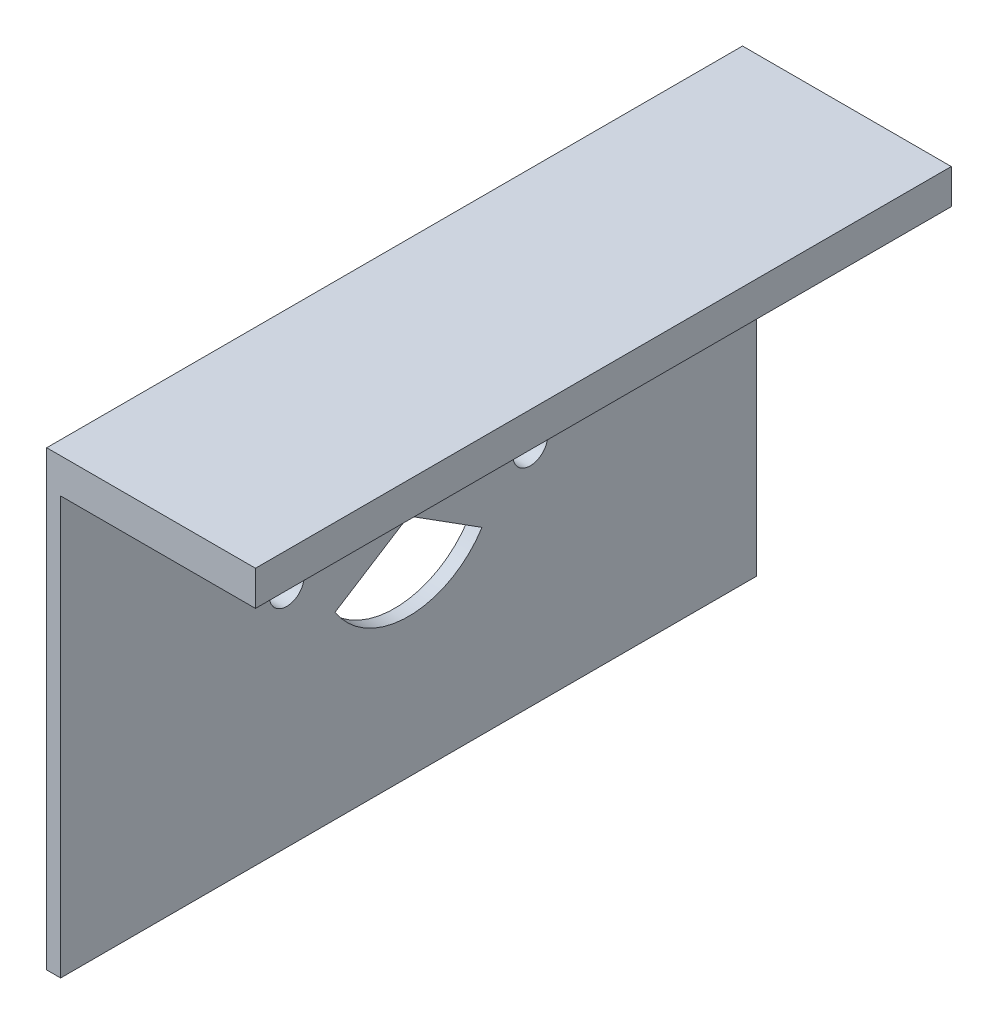
SolidWorks part; units mm, degrees
ref_plane "Front Plane" through (0, 0, 0) normal (0, 0, 1) x (1, 0, 0)
ref_plane "Top Plane" through (0, 0, 0) normal (0, 1, 0) x (1, 0, 0)
ref_plane "Right Plane" through (0, 0, 0) normal (1, 0, 0) x (0, 0, -1)
sketch "Sketch1" plane through (0, 0, 0) normal (1, 0, 0) x (0, 0, -1)
  line L0 (0, 0) -> (-10.5574, -6.6926)
  line L1 (-50, -32.5) -> (50, -32.5)
  line L2 (-50, -32.5) -> (-50, 32.5)
  line L3 (-50, 32.5) -> (50, 32.5)
  line L4 (50, -32.5) -> (50, 32.5)
  line L5 (-50, -32.5) -> (50, 32.5) construction
  line L6 (-50, 32.5) -> (50, -32.5) construction
  line L7 (0, 0) -> (10.5574, -6.6926)
  line L8 (-50, 32.5) -> (-50, 27.5)
  line L9 (-50, 27.5) -> (50, 27.5)
  line L10 (-50, 0) -> (50, 0)
  circle A0 centre (0, 0) radius 12.5
  circle A1 centre (-17.5, 0) radius 2.5
  circle A2 centre (17.5, 0) radius 2.5
  point P0 (0, 0)
  point P8 (-10.5574, -6.6926)
  point P9 (10.5574, -6.6926)
  point P12 (-50, 27.5)
  point P13 (50, 27.5)
  point P18 (-17.5, 0)
  point P19 (17.5, 0)
  dimension "D3" = 25
  dimension "D8" = 5
  dimension "D9" = 5
  dimension "D1" = 100
  dimension "D2" = 65
  dimension "D4" = 5
  dimension "D5" = 5
  dimension "D6" = 17.5
  dimension "D7" = 17.5
extrude "Boss-Extrude5" add sketch "Sketch1" along normal blind 2 contours L2 L9 L4 L3 | A2 L10 L4 L9 L2 A1 A0 | L10 A0 | L10 A0 L0 | L7 A0 L10 | A2 L10 A0 A1 L2 L1 L4
sketch "Sketch4" plane through (2, 0, 0) normal (1, 0, 0) x (0, 0, -1)
  line L0 (-50, -32.5) -> (-50, 32.5) construction
  line L1 (50, -32.5) -> (50, 32.5) construction
  line L2 (-50, 27.5) -> (50, 27.5)
  line L3 (50, 27.5) -> (50, 32.5)
  line L4 (50, 32.5) -> (-50, 32.5)
  line L5 (-50, 32.5) -> (-50, 27.5)
  point P0 (-50, 32.5)
  point P1 (-50, 27.5)
  point P3 (50, 32.5)
  point P6 (50, 27.5)
  dimension "D1" = 5
  dimension "D2" = 5
extrude "Boss-Extrude6" add sketch "Sketch4" along normal blind 28
